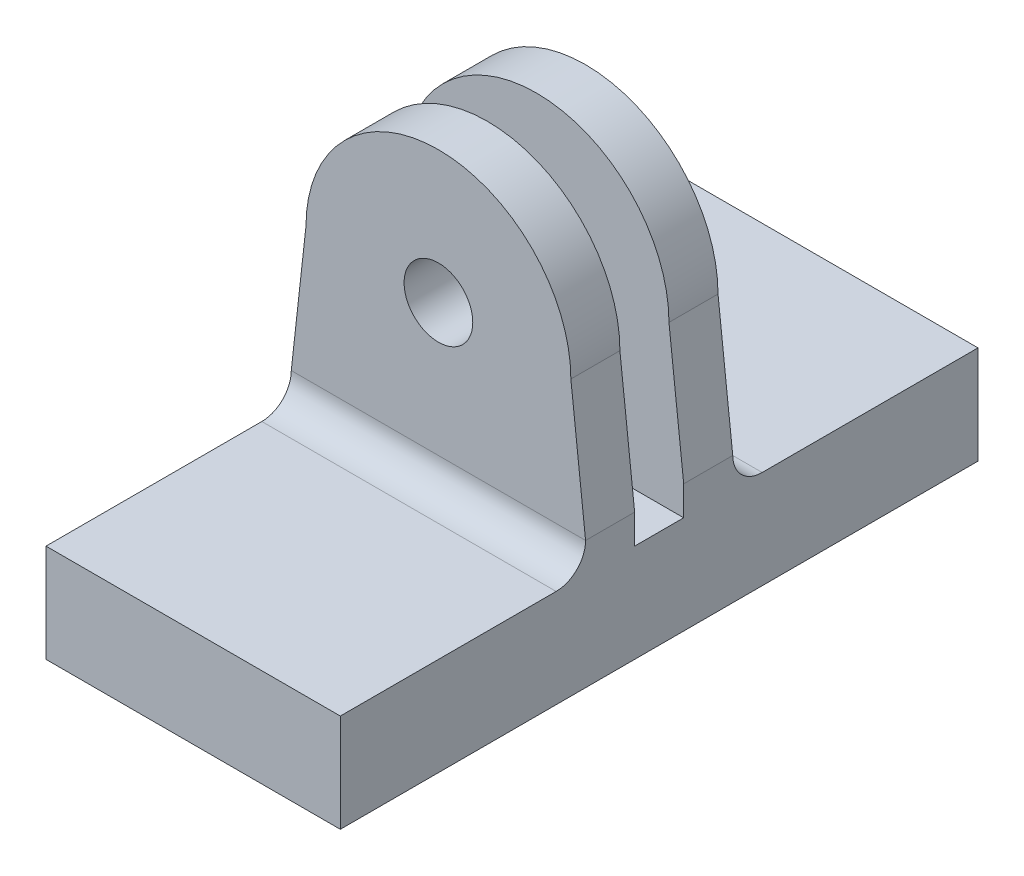
SolidWorks part; units mm, degrees
ref_plane "Front Plane" through (0, 0, 0) normal (0, 0, 1) x (1, 0, 0)
ref_plane "Top Plane" through (0, 0, 0) normal (0, 1, 0) x (1, 0, 0)
ref_plane "Right Plane" through (0, 0, 0) normal (1, 0, 0) x (0, 0, -1)
sketch "Sketch2" plane through (0, 0, 0) normal (0, 1, 0) x (1, 0, 0)
  line L1 (0, 0) -> (30, 0)
  line L2 (0, 0) -> (0, 65)
  line L3 (0, 65) -> (30, 65)
  line L4 (30, 0) -> (30, 65)
  dimension "D1" = 65
  dimension "D2" = 30
extrude "Boss-Extrude1" add sketch "Sketch2" along normal blind 10
sketch "Sketch4" plane through (30, 0, 0) normal (1, 0, 0) x (0, 0, -1)
  line L0 (30, 10) -> (30, 40)
  line L1 (32.5, 10) -> (32.5, 24.1477) construction
  line L2 (0, 10) -> (65, 10) construction
  line L3 (30, 40) -> (25, 40)
  line L4 (25, 40) -> (25, 13)
  line L6 (43, 10) -> (35, 10)
  line L7 (22, 10) -> (30, 10)
  line L8 (40, 40) -> (40, 13)
  line L9 (35, 40) -> (40, 40)
  line L10 (35, 10) -> (35, 40)
  arc A0 (22, 10) -> (25, 13) centre (22, 13) ccw
  arc A1 (43, 10) -> (40, 13) centre (43, 13) cw
  point P12 (25, 10)
  point P18 (40, 10)
  dimension "D3" = 3
  dimension "D1" = 2.5
  dimension "D2" = 5
  dimension "D4" = 30
extrude "Boss-Extrude2" add sketch "Sketch4" against normal up to surface (30 mm away) up to face at (0, 5, -32.5)
sketch "Sketch5" plane through (0, 0, -40) normal (0, 0, -1) x (-1, 0, 0)
  line L0 (-15, 26.5) -> (-15, 40) construction
  line L1 (0, 13) -> (0, 40)
  line L3 (-30, 13) -> (-30, 40)
  line L4 (-28.5, 26.5) -> (-30, 13)
  line L5 (-1.5, 26.5) -> (0, 13)
  line L6 (0, 40) -> (0, 41.8817)
  line L7 (0, 41.8817) -> (-30, 41.8817)
  line L8 (-30, 41.8817) -> (-30, 40)
  arc A0 (-1.5, 26.5) -> (-28.5, 26.5) centre (-15, 26.5) ccw
extrude "Cut-Extrude1" cut sketch "Sketch5" against normal through all
sketch "Sketch6" plane through (0, 0, -40) normal (0, 0, -1) x (-1, 0, 0)
  line L0 (-28.5, 26.5) -> (-1.5, 26.5) construction
  circle A0 centre (-15, 26.5) radius 3.5
  dimension "D1" = 7
  dimension "D2" = 27
extrude "Cut-Extrude2" cut sketch "Sketch6" against normal through all
